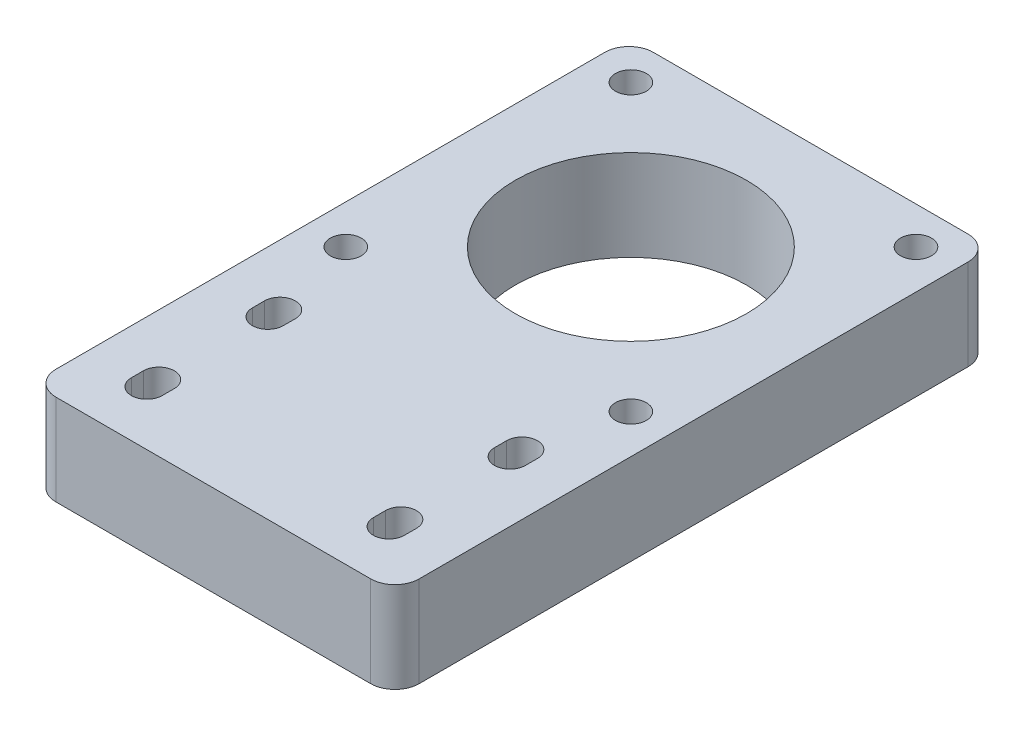
SolidWorks part; units mm, degrees
ref_plane "Front Plane" through (0, 0, 0) normal (0, 0, 1) x (1, 0, 0)
ref_plane "Top Plane" through (0, 0, 0) normal (0, 1, 0) x (1, 0, 0)
ref_plane "Right Plane" through (0, 0, 0) normal (1, 0, 0) x (0, 0, -1)
sketch "Sketch1" plane through (0, 0, 0) normal (0, 1, 0) x (1, 0, 0)
  line L3 (-26, 29.7) -> (26, 29.7)
  line L5 (0, -55) -> (0, 55) construction
  line L6 (-55, 0) -> (55, 0) construction
  line L19 (-22.55, -37.98) -> (-22.55, -39.98)
  line L20 (-17.45, -37.98) -> (-17.45, -39.98)
  line L35 (-22.55, -59.98) -> (-22.55, -57.98)
  line L37 (-17.45, -59.98) -> (-17.45, -57.98)
  line L38 (-22.55, -59.98) -> (-17.45, -57.98) construction
  line L39 (-22.55, -57.98) -> (-17.45, -59.98) construction
  line L40 (-26, -68.98) -> (26, -68.98)
  line L42 (-30, 25.7) -> (-30, -64.98)
  line L43 (30, 25.7) -> (30, -64.98)
  line L44 (-22.55, -37.98) -> (-17.45, -39.98) construction
  line L45 (-22.55, -39.98) -> (-17.45, -37.98) construction
  line L46 (17.45, -37.98) -> (17.45, -39.98)
  line L47 (22.55, -37.98) -> (22.55, -39.98)
  line L48 (22.55, -59.98) -> (22.55, -57.98)
  line L49 (17.45, -59.98) -> (17.45, -57.98)
  circle A0 centre (0, 0) radius 19.1
  circle A1 centre (-23.55, 23.55) radius 2.55
  circle A2 centre (23.55, 23.55) radius 2.55
  circle A3 centre (23.55, -23.55) radius 2.55
  circle A4 centre (-23.55, -23.55) radius 2.55
  arc A7 (-22.55, -37.98) -> (-17.45, -37.98) centre (-20, -37.98) cw
  arc A12 (-22.55, -39.98) -> (-17.45, -39.98) centre (-20, -39.98) ccw
  arc A23 (-22.55, -57.98) -> (-17.45, -57.98) centre (-20, -57.98) cw
  arc A24 (-22.55, -59.98) -> (-17.45, -59.98) centre (-20, -59.98) ccw
  arc A25 (-26, -68.98) -> (-30, -64.98) centre (-26, -64.98) cw
  arc A26 (26, -68.98) -> (30, -64.98) centre (26, -64.98) ccw
  arc A27 (30, 25.7) -> (26, 29.7) centre (26, 25.7) ccw
  arc A28 (-26, 29.7) -> (-30, 25.7) centre (-26, 25.7) ccw
  arc A29 (22.55, -39.98) -> (17.45, -39.98) centre (20, -39.98) cw
  arc A30 (22.55, -37.98) -> (17.45, -37.98) centre (20, -37.98) ccw
  arc A31 (22.55, -57.98) -> (17.45, -57.98) centre (20, -57.98) ccw
  arc A32 (22.55, -59.98) -> (17.45, -59.98) centre (20, -59.98) cw
  point P20 (-20, -58.98)
  point P22 (-50.0429, -38.98)
  point P38 (30, 29.7)
  point P41 (-30, 29.7)
  point P43 (-20, -38.98)
  point P44 (-22.55, -38.98)
  point P46 (0, 0)
  dimension "D1" = 38.2
  dimension "D4" = 5.1
  dimension "D3" = 98.68
  dimension "D11" = 2
  dimension "D15" = 2
  dimension "D12" = 4
  dimension "D18" = 2.55
  dimension "D2" = 60
  dimension "D5" = 6.15
  dimension "D6" = 6.45
  dimension "D7" = 29.7
  dimension "D8" = 5.1
  dimension "D9" = 30
  dimension "D10" = 10
  dimension "D13" = 0
  dimension "D14" = 20
  dimension "D16" = 10
  dimension "D17" = 2
extrude "Boss-Extrude1" add sketch "Sketch1" along normal blind 15
